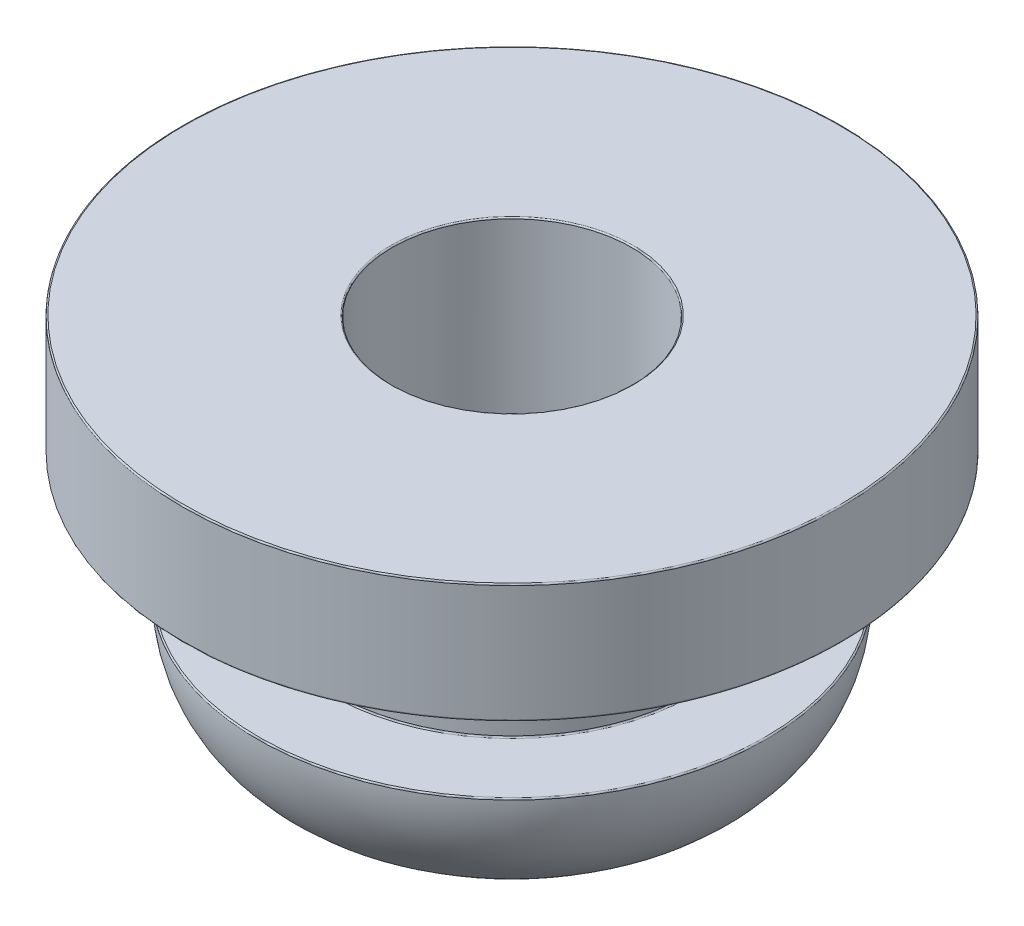
SolidWorks part; units mm, degrees
material "Rubber"
ref_plane "Front" through (0, 0, 0) normal (0, 0, 1) x (1, 0, 0)
ref_plane "Top" through (0, 0, 0) normal (0, 1, 0) x (1, 0, 0)
ref_plane "Right" through (0, 0, 0) normal (1, 0, 0) x (0, 0, -1)
sketch "Sketch1" plane through (0, 0, 0) normal (0, 0, 1) x (1, 0, 0)
  line L0 (-1.5875, 0) -> (1.5875, 0) construction
  line L1 (-2.3813, 0) -> (2.3813, 0) construction
  line L2 (0, 2.3685) -> (0, -2.394) construction
  line L3 (2.3813, 0.7937) -> (2.3813, -0.7937) construction
  line L4 (-4.3656, 2.3685) -> (4.3656, 2.3686) construction
  line L5 (3.3734, -0.7937) -> (-3.3734, -0.7938) construction
  point P13 (0, -0.7938)
  dimension "ID" = 3.175
  dimension "for hole dia" = 4.7625
  dimension "material thick" = 1.5875
  dimension "flange dia top" = 8.7312
  dimension "flange dia bottom" = 6.7469
  dimension "Top Thickness" = 1.5748
  dimension "Bottom Thickness" = 1.6002
sketch "Sketch2" plane through (0, 0, 0) normal (0, 0, 1) x (1, 0, 0)
  line L0 (2.3813, 0.7937) -> (2.3813, -0.7937)
  line L1 (2.3813, -0.7937) -> (3.3734, -0.7937)
  line L2 (1.5875, 2.3685) -> (1.5875, -2.394)
  line L3 (-4.3656, 2.3685) -> (4.3656, 2.3685) construction
  line L4 (1.5875, -2.394) -> (2.3813, -2.394)
  line L5 (2.3813, 0.7937) -> (4.3656, 0.7937)
  line L6 (4.3656, 0.7937) -> (4.3656, 2.3686)
  line L7 (4.3656, 2.3686) -> (1.5875, 2.3685)
  line L8 (3.3734, -0.7937) -> (3.3734, -2.394) construction
  arc A0 (2.3813, -2.394) -> (3.3734, -0.7937) centre (1.5869, -0.7938) ccw
revolve "Revolve1" add sketch "Sketch2" angle 360 about L2
fillet "Fillet1" radius 0.0175 8 edges at (-2.3813, 0.7937, 0) (-4.3656, 0.7937, 0) (-2.3813, -0.7937, 0) (-1.5875, -2.394, 0) (-4.3656, 2.3686, 0) (-1.5875, 2.3685, 0) (-3.3734, -0.7937, 0) (-2.3813, -2.3939, 0)
equation "\"D1@Fillet1\"=\"flange dia top@Sketch1\"*.002"
